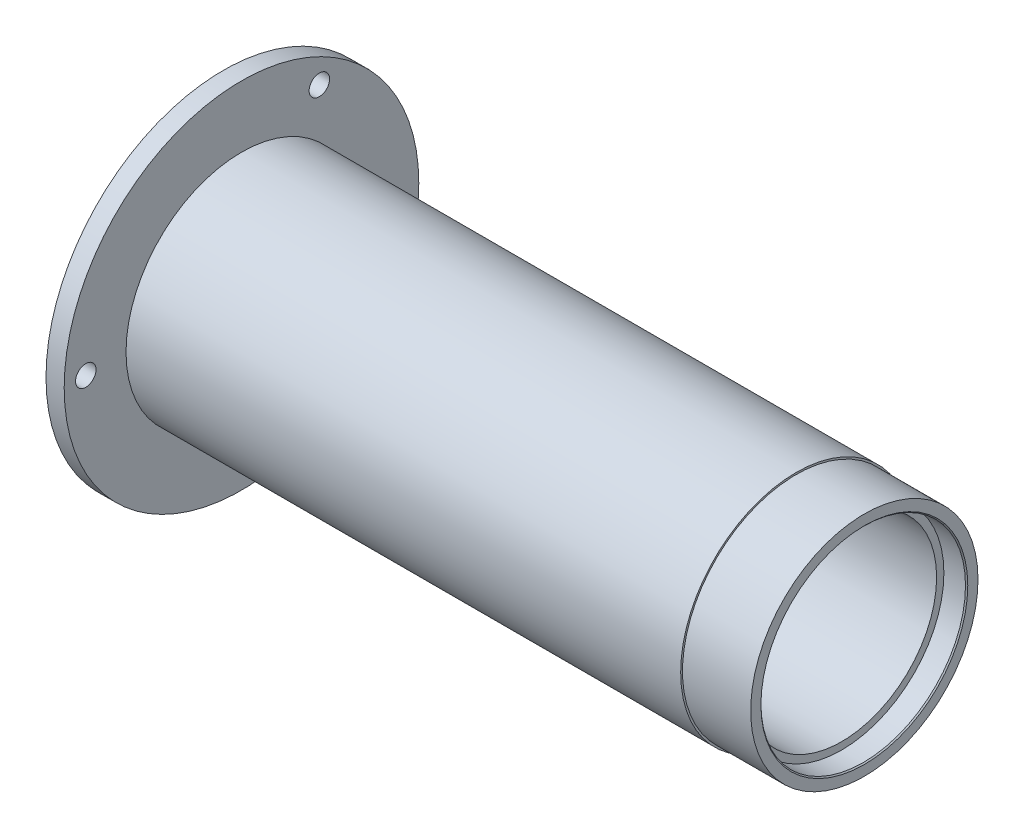
SolidWorks part; units mm, degrees
ref_plane "正面" through (0, 0, 0) normal (0, 0, 1) x (1, 0, 0)
ref_plane "平面" through (0, 0, 0) normal (0, 1, 0) x (1, 0, 0)
ref_plane "右側面" through (0, 0, 0) normal (1, 0, 0) x (0, 0, -1)
sketch "ｽｹｯﾁ1" plane through (0, 0, 0) normal (1, 0, 0) x (0, 0, -1)
  circle A0 centre (0, 0) radius 78
extrude "ﾎﾞｽ - 押し出し1" add sketch "ｽｹｯﾁ1" along normal blind 8
sketch "ｽｹｯﾁ2" plane through (0, 0, 0) normal (1, 0, 0) x (0, 0, -1)
  circle A0 centre (0, 0) radius 50.8
extrude "ﾎﾞｽ - 押し出し2" add sketch "ｽｹｯﾁ2" along normal blind 252
sketch "ｽｹｯﾁ3" plane through (0, 0, 0) normal (1, 0, 0) x (0, 0, -1)
  circle A0 centre (0, 0) radius 50
extrude "ﾎﾞｽ - 押し出し3" add sketch "ｽｹｯﾁ3" along normal blind 282
sketch "ｽｹｯﾁ4" plane through (0, 0, 0) normal (1, 0, 0) x (0, 0, -1)
  circle A0 centre (0, 0) radius 41.8
extrude "ｶｯﾄ - 押し出し1" cut sketch "ｽｹｯﾁ4" against normal through all and the other way through all
sketch "ｽｹｯﾁ5" plane through (0, 0, 0) normal (1, 0, 0) x (0, 0, -1)
  circle A0 centre (0, 0) radius 45
sketch "ｽｹｯﾁ6" plane through (0, 0, 0) normal (1, 0, 0) x (0, 0, -1)
  circle A0 centre (0, 0) radius 45
extrude "ｶｯﾄ - 押し出し3" cut sketch "ｽｹｯﾁ6" along normal blind 10
ref_plane "平面1" through (282, 0, 0) normal (1, 0, 0) x (0, 0, -1)
sketch "ｽｹｯﾁ7" plane through (282, 0, 0) normal (1, 0, 0) x (0, 0, -1)
  circle A0 centre (0, 0) radius 45
extrude "ｶｯﾄ - 押し出し4" cut sketch "ｽｹｯﾁ7" against normal blind 10
sketch "ｽｹｯﾁ8" plane through (0, 0, 0) normal (1, 0, 0) x (0, 0, -1)
  circle A0 centre (-68.5, 0) radius 4.5
  circle A1 centre (34.25, 59.3227) radius 4.5
  circle A2 centre (34.25, -59.3227) radius 4.5
extrude "ｶｯﾄ - 押し出し5" cut sketch "ｽｹｯﾁ8" against normal through all and the other way through all
chamfer "面取り1" distance 0.5 angle 45 1 edges at (0, 0, -45)
chamfer "面取り2" distance 0.5 angle 45 1 edges at (282, 0, -45)
